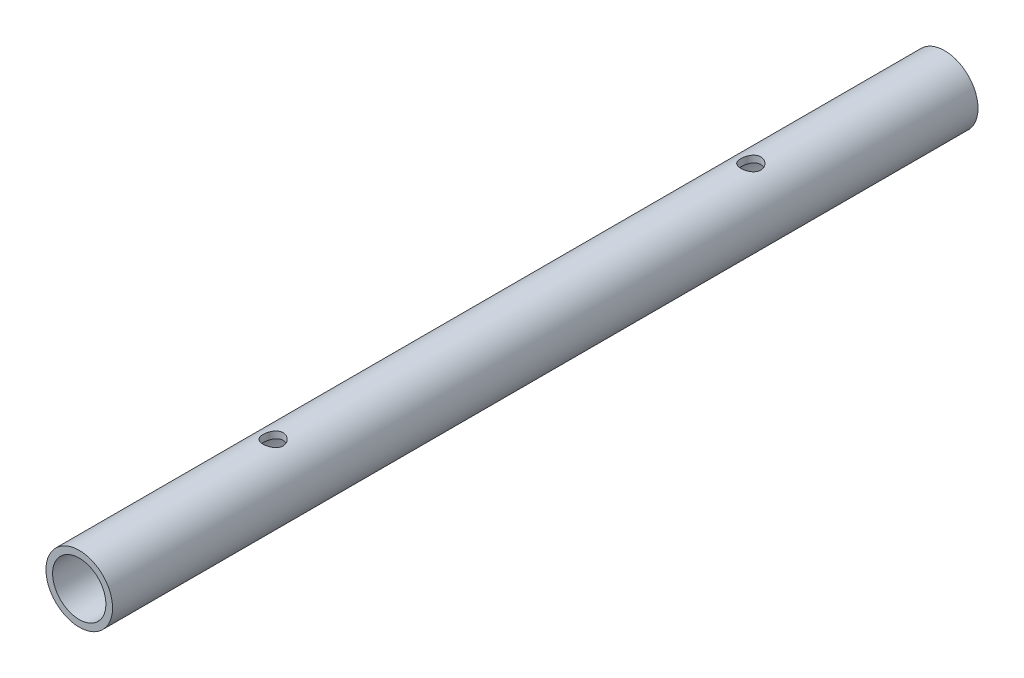
SolidWorks part; units mm, degrees
ref_plane "Plan de face" through (0, 0, 0) normal (0, 0, 1) x (1, 0, 0)
ref_plane "Plan de dessus" through (0, 0, 0) normal (0, 1, 0) x (1, 0, 0)
ref_plane "Plan de droite" through (0, 0, 0) normal (1, 0, 0) x (0, 0, -1)
sketch "Sketch1" plane through (0, 0, 0) normal (0, 0, 1) x (1, 0, 0)
  circle A0 centre (0, 0) radius 5
extrude "Boss-Extrude1" add sketch "Sketch1" along normal blind 129.931
sketch "Sketch2" plane through (0, 0, 129.931) normal (0, 0, 1) x (1, 0, 0)
  circle A0 centre (0, 0) radius 4
extrude "Cut-Extrude1" cut sketch "Sketch2" against normal up to next
sketch "Sketch5" plane through (0, 0, 0) normal (0, 1, 0) x (1, 0, 0)
  circle A0 centre (0, -29.104) radius 1.5
  circle A1 centre (0, -100.826) radius 1.5
  dimension "D1" = 29.104
  dimension "D2" = 100.826
extrude "Cut-Extrude2" cut sketch "Sketch5" against normal through all and the other way through all
